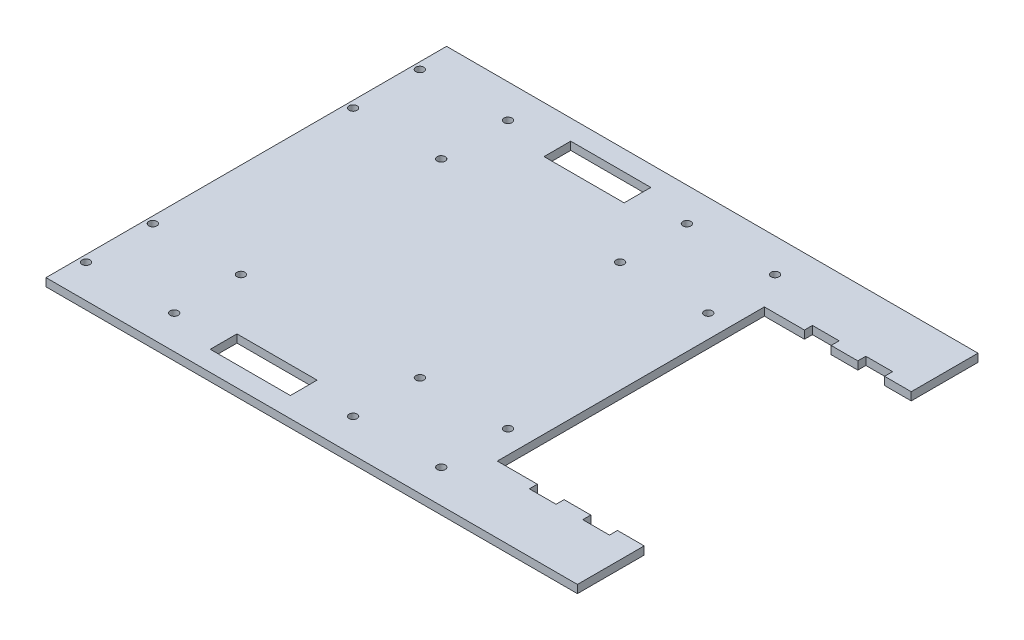
SolidWorks part; units mm, degrees
ref_plane "Front Plane" through (0, 0, 0) normal (0, 0, 1) x (1, 0, 0)
ref_plane "Top Plane" through (0, 0, 0) normal (0, 1, 0) x (1, 0, 0)
ref_plane "Right Plane" through (0, 0, 0) normal (1, 0, 0) x (0, 0, -1)
sketch "Sketch2" plane through (0, 0, 0) normal (0, 1, 0) x (1, 0, 0)
  line L1 (-90, -75) -> (90, -75)
  line L2 (-90, -75) -> (-90, 75)
  line L3 (-90, 75) -> (90, 75)
  line L4 (90, -75) -> (90, 75)
  line L5 (0, 75) -> (0, -75) construction
  line L6 (-90, 0) -> (90, 0) construction
  point P0 (0, 0)
  dimension "D1" = 180
  dimension "D2" = 150
extrude "Boss-Extrude1" add sketch "Sketch2" along normal blind 3
sketch "Sketch4" plane through (0, 3, 0) normal (0, 1, 0) x (1, 0, 0)
  line L0 (-90, 0) -> (90, 0) construction
  line L1 (-90, 75) -> (-90, -75) construction
  line L2 (90, -75) -> (90, 75) construction
  line L3 (0, 75) -> (0, -75) construction
  line L4 (90, 75) -> (-90, 75) construction
  line L5 (-90, -75) -> (90, -75) construction
  line L9 (-69, -62.49) -> (-31, -62.49) construction
  line L11 (-66.5, -37.49) -> (-36.2934, -37.49) construction
  line L13 (-90, -75) -> (90, -75) construction
  circle A0 centre (-66.5, -62.49) radius 1.5
  circle A1 centre (-66.5, -37.49) radius 1.5
  circle A2 centre (-33.5, -62.49) radius 1.5
  circle A3 centre (-33.5, -37.49) radius 1.5
  circle A4 centre (-66.5, 62.49) radius 1.5
  circle A5 centre (-66.5, 37.49) radius 1.5
  circle A6 centre (-33.5, 62.49) radius 1.5
  circle A7 centre (-33.5, 37.49) radius 1.5
  circle A8 centre (66.5, -62.49) radius 1.5
  circle A9 centre (33.5, -62.49) radius 1.5
  circle A10 centre (33.5, -37.49) radius 1.5
  circle A11 centre (66.5, -37.49) radius 1.5
  circle A12 centre (66.5, 37.49) radius 1.5
  circle A13 centre (66.5, 62.49) radius 1.5
  circle A14 centre (33.5, 62.49) radius 1.5
  circle A15 centre (33.5, 37.49) radius 1.5
  dimension "D2" = 12.51
  dimension "D3" = 25
extrude "Cut-Extrude1" cut sketch "Sketch4" against normal blind 3
sketch "Sketch5" plane through (0, 0, 0) normal (0, -1, 0) x (1, 0, 0)
  line L0 (90, 75) -> (90, -75) construction
  line L1 (105, -50) -> (75, -50)
  line L2 (105, -50) -> (105, 50)
  line L3 (105, 50) -> (75, 50)
  line L4 (75, -50) -> (75, 50)
  line L5 (90, 50) -> (90, -50) construction
  line L6 (105, 0) -> (75, 0) construction
  point P0 (90, 0)
  dimension "D1" = 100
  dimension "D2" = 30
extrude "Cut-Extrude2" cut sketch "Sketch5" against normal blind 3
sketch "Sketch7" plane through (0, 3, 0) normal (0, 1, 0) x (1, 0, 0)
  line L0 (90, -50) -> (130, -50)
  line L9 (90, -75) -> (130, -75)
  line L10 (130, -75) -> (130, -50)
  line L11 (90, 50) -> (130, 50)
  line L12 (90, 75) -> (130, 75)
  line L13 (130, 75) -> (130, 50)
  line L14 (90, 50) -> (90, 75)
  line L15 (90, -75) -> (90, -50)
  dimension "D1" = 40
  dimension "D2" = 40
extrude "Boss-Extrude4" add sketch "Sketch7" against normal blind 3
sketch "Sketch8" plane through (0, 3, 0) normal (0, 1, 0) x (1, 0, 0)
  line L0 (120, 50) -> (120, 75) construction
  line L1 (75, 50) -> (130, 50) construction
  line L2 (130, 75) -> (-90, 75) construction
  line L3 (130, 50) -> (130, 75) construction
  line L4 (130, 53) -> (74.8723, 53) construction
  line L5 (100, 50) -> (100, 53) construction
  line L6 (120, 50) -> (110, 50)
  line L7 (120, 50) -> (120, 53)
  line L8 (120, 53) -> (110, 53)
  line L9 (110, 50) -> (110, 53)
  line L10 (75, 0) -> (134.9156, 0) construction
  line L11 (100, 50) -> (90, 50)
  line L12 (100, 50) -> (100, 53)
  line L13 (100, 53) -> (90, 53)
  line L14 (90, 50) -> (90, 53)
  line L15 (75, -50) -> (75, 50) construction
  line L16 (120, -53) -> (110, -53)
  line L17 (110, -50) -> (110, -53)
  line L18 (120, -50) -> (110, -50)
  line L19 (120, -50) -> (120, -53)
  line L20 (100, -53) -> (90, -53)
  line L21 (90, -50) -> (90, -53)
  line L22 (100, -50) -> (90, -50)
  line L23 (100, -50) -> (100, -53)
  dimension "D1" = 10
  dimension "D2" = 3
  dimension "D3" = 10
  dimension "D4" = 10
  dimension "D5" = 10
extrude "Cut-Extrude4" cut sketch "Sketch8" against normal blind 10
sketch "Sketch9" plane through (0, 3, 0) normal (0, 1, 0) x (1, 0, 0)
  line L0 (130, 75) -> (-90, 75) construction
  line L1 (-90, -75) -> (-69, -75)
  line L2 (-90, -75) -> (-90, 75)
  line L3 (-90, 75) -> (-69, 75)
  line L4 (-69, -75) -> (-69, 75)
  circle A0 centre (-66.5, 62.49) radius 1.5 construction
  dimension "D1" = 2.5
extrude "Cut-Extrude5" cut sketch "Sketch9" against normal blind 10
sketch "Sketch10" plane through (0, 3, 0) normal (0, 1, 0) x (1, 0, 0)
  line L0 (33.5, 62.49) -> (-33.5, 62.49) construction
  line L1 (75, 0) -> (-69, 0) construction
  line L2 (75, -50) -> (75, 50) construction
  line L3 (-69, -75) -> (-69, 75) construction
  line L4 (15, -57.49) -> (-15, -57.49)
  line L5 (15, 67.49) -> (-15, 67.49)
  line L6 (15, 67.49) -> (15, 57.49)
  line L7 (15, 57.49) -> (-15, 57.49)
  line L8 (-15, 67.49) -> (-15, 57.49)
  line L9 (0, 57.49) -> (0, 67.49) construction
  line L10 (15, 62.49) -> (-15, 62.49) construction
  line L11 (-15, -67.49) -> (-15, -57.49)
  line L12 (15, -67.49) -> (-15, -67.49)
  line L13 (15, -67.49) -> (15, -57.49)
  point P10 (0, 62.49)
  dimension "D1" = 10
  dimension "D2" = 30
extrude "Cut-Extrude6" cut sketch "Sketch10" against normal blind 10
